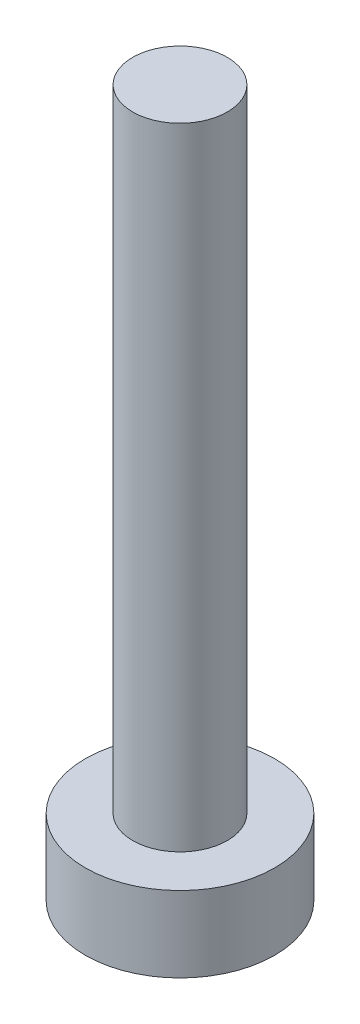
SolidWorks part; units mm, degrees
ref_plane "Front Plane" through (0, 0, 0) normal (0, 0, 1) x (1, 0, 0)
ref_plane "Top Plane" through (0, 0, 0) normal (0, 1, 0) x (1, 0, 0)
ref_plane "Right Plane" through (0, 0, 0) normal (1, 0, 0) x (0, 0, -1)
sketch "Эскиз1" plane through (0, 0, 0) normal (0, 1, 0) x (1, 0, 0)
  circle A0 centre (0, 0) radius 3
extrude "Бобышка-Вытянуть1" add sketch "Эскиз1" along normal blind 2.4
sketch "Эскиз2" plane through (0, 2.4, 0) normal (0, 1, 0) x (1, 0, 0)
  circle A0 centre (0, 0) radius 1.5
extrude "Бобышка-Вытянуть2" add sketch "Эскиз2" along normal blind 20
